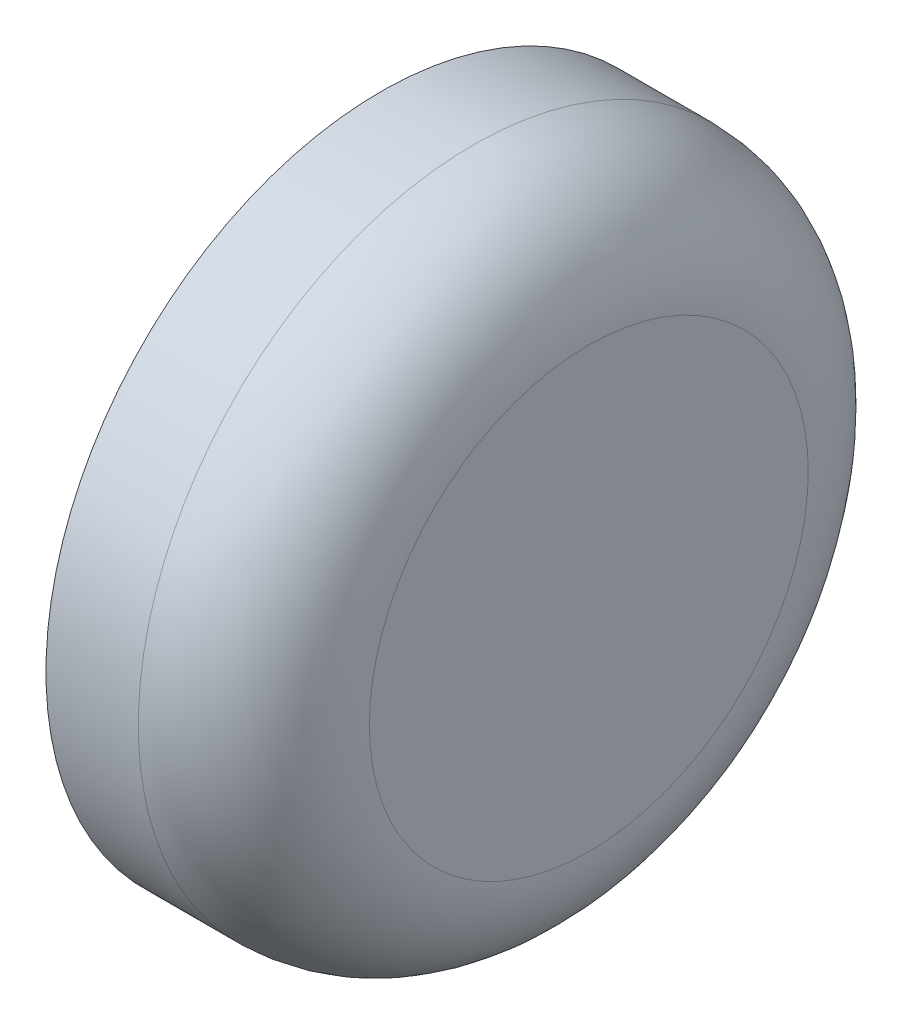
SolidWorks part; units mm, degrees
ref_plane "Front Plane" through (0, 0, 0) normal (0, 0, 1) x (1, 0, 0)
ref_plane "Top Plane" through (0, 0, 0) normal (0, 1, 0) x (1, 0, 0)
ref_plane "Right Plane" through (0, 0, 0) normal (1, 0, 0) x (0, 0, -1)
sketch "Sketch2" plane through (0, 0, 0) normal (1, 0, 0) x (0, 0, -1)
  circle A0 centre (0, 0) radius 7.25
  dimension "D1" = 14.5
extrude "Boss-Extrude1" add sketch "Sketch2" along normal blind 4.5
fillet "Fillet1" radius 2.5 1 edges at (4.5, 0, -7.25)
sketch "Sketch3" plane through (0, 0, 0) normal (-1, 0, 0) x (0, 0, 1)
  circle A0 centre (0, 0) radius 3.3
  dimension "D1" = 6.6
extrude "Cut-Extrude1" cut sketch "Sketch3" against normal blind 1
